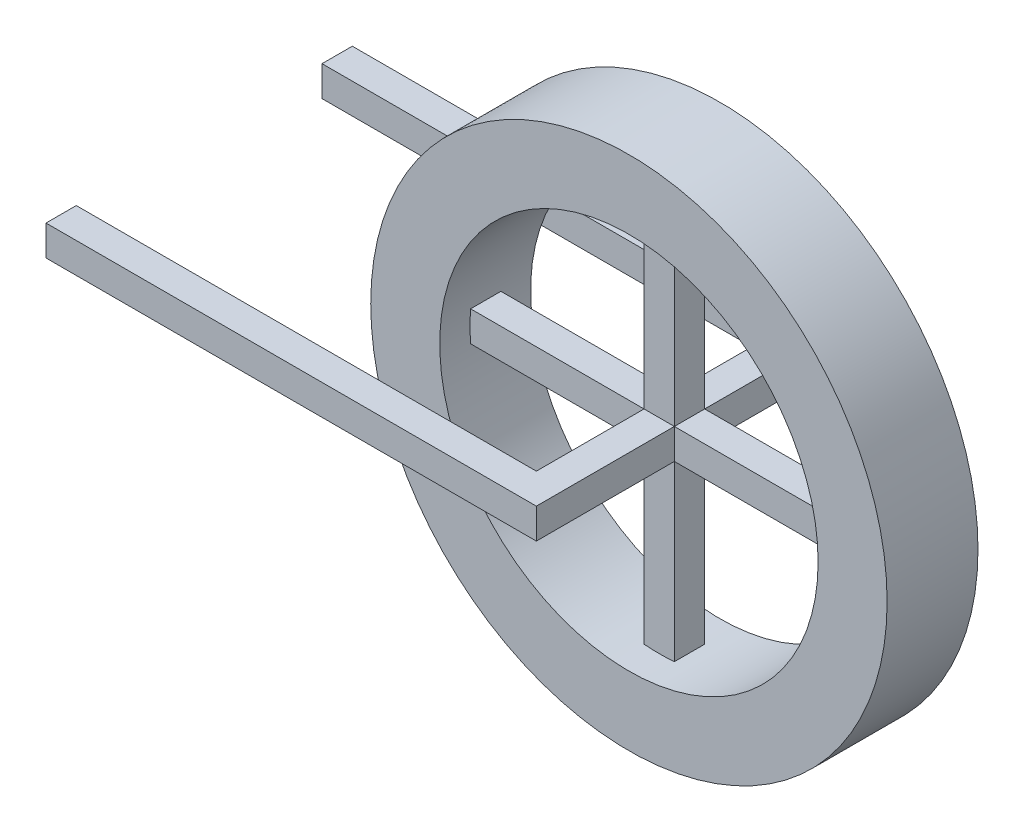
SolidWorks part; units mm, degrees
ref_plane "Plan de face" through (0, 0, 0) normal (0, 0, 1) x (1, 0, 0)
ref_plane "Plan de dessus" through (0, 0, 0) normal (0, 1, 0) x (1, 0, 0)
ref_plane "Plan de droite" through (0, 0, 0) normal (1, 0, 0) x (0, 0, -1)
sketch "Esquisse1" plane through (0, 0, 0) normal (0, 0, 1) x (1, 0, 0)
  circle A0 centre (0, 0) radius 56.125
  circle A1 centre (0, 0) radius 41.125
  dimension "D1" = 112.25
  dimension "D2" = 15
extrude "Boss.-Extru.1" add sketch "Esquisse1" along normal blind 19.75
sketch "Esquisse2" plane through (0, 0, 0) normal (1, 0, 0) x (0, 0, -1)
  line L1 (-13.1667, 3.2917) -> (-6.5833, 3.2917)
  line L2 (-13.1667, 3.2917) -> (-13.1667, -3.2917)
  line L3 (-13.1667, -3.2917) -> (-6.5833, -3.2917)
  line L4 (-6.5833, 3.2917) -> (-6.5833, -3.2917)
  line L6 (-19.75, 3.2917) -> (-13.1667, 3.2917) construction
  line L7 (-19.75, 56.125) -> (-19.75, -56.125) construction
  line L8 (-6.5833, 3.2917) -> (0, 3.2917) construction
  line L9 (0, -56.125) -> (0, 56.125) construction
  point P8 (-13.1667, 0)
extrude "Boss.-Extru.2" add sketch "Esquisse2" along normal up to surface and the other way up to surface up to face at (41.125, 0, 19.75) other way up to face at (41.125, 0, 19.75)
sketch "Esquisse4" plane through (0, 0, 0) normal (1, 0, 0) x (0, 0, -1)
  line L0 (-32.1186, 0) -> (20.7393, 0) construction
pattern_circular "Répétition circulaire1" count 2 every 90 about axis through (0, 0, 32.1186) along (0, 0, -1) of "Boss.-Extru.2"
sketch "Esquisse5" plane through (0, 0, 6.5833) normal (0, 0, -1) x (-1, 0, 0)
  line L1 (-3.2917, 3.2917) -> (3.2917, 3.2917)
  line L2 (-3.2917, 3.2917) -> (-3.2917, -3.2917)
  line L3 (-3.2917, -3.2917) -> (3.2917, -3.2917)
  line L4 (3.2917, 3.2917) -> (3.2917, -3.2917)
extrude "Boss.-Extru.3" add sketch "Esquisse5" along normal blind 30
sketch "Esquisse6" plane through (-3.2917, 0, 0) normal (-1, 0, 0) x (0, 0, 1)
  line L0 (-23.4167, -3.2917) -> (6.5833, -3.2917) construction
  line L1 (-23.4167, 3.2917) -> (-16.8333, 3.2917)
  line L2 (-23.4167, 3.2917) -> (-23.4167, -3.2917)
  line L3 (-23.4167, -3.2917) -> (-16.8333, -3.2917)
  line L4 (-16.8333, 3.2917) -> (-16.8333, -3.2917)
extrude "Boss.-Extru.4" add sketch "Esquisse6" along normal blind 100
ref_plane "Plan1" through (0, 0, 9.875) normal (0, 0, -1) x (-1, 0, 0)
mirror "Symétrie1" about plane through (0, 0, 9.875) normal (0, 0, -1) of "Boss.-Extru.4", "Boss.-Extru.3"
